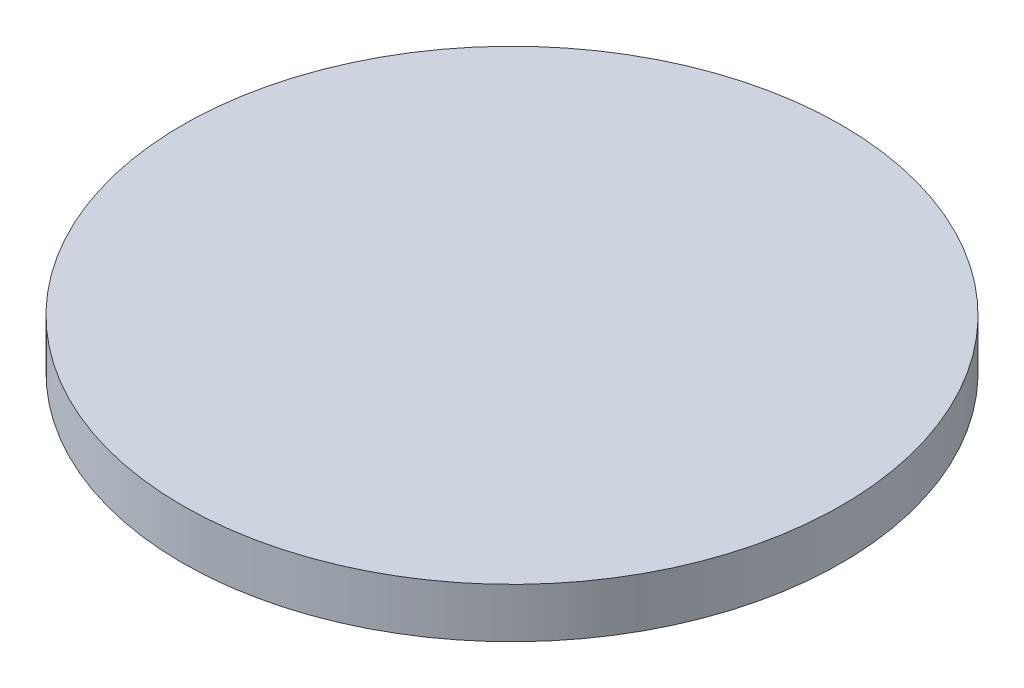
SolidWorks part; units mm, degrees
ref_plane "Front Plane" through (0, 0, 0) normal (0, 0, 1) x (1, 0, 0)
ref_plane "Top Plane" through (0, 0, 0) normal (0, 1, 0) x (1, 0, 0)
ref_plane "Right Plane" through (0, 0, 0) normal (1, 0, 0) x (0, 0, -1)
sketch "Sketch1" plane through (0, 0, 0) normal (0, 1, 0) x (1, 0, 0)
  circle A0 centre (0, 0) radius 8.9535
  dimension "D1" = 17.907
extrude "Boss-Extrude1" add sketch "Sketch1" along normal blind 1.35
